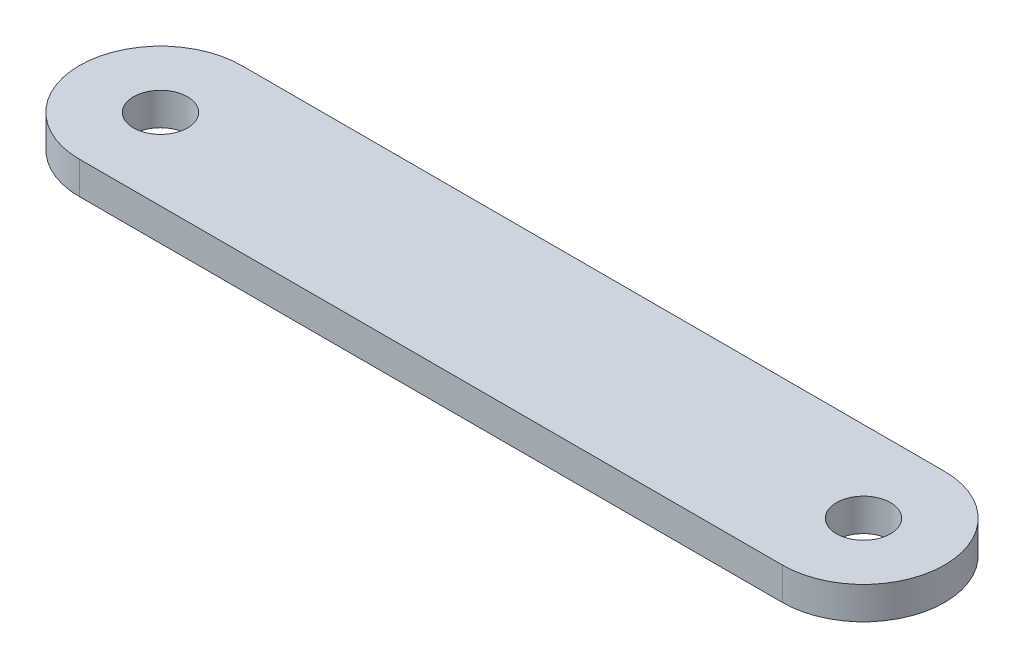
SolidWorks part; units mm, degrees
ref_plane "Front Plane" through (0, 0, 0) normal (0, 0, 1) x (1, 0, 0)
ref_plane "Top Plane" through (0, 0, 0) normal (0, 1, 0) x (1, 0, 0)
ref_plane "Right Plane" through (0, 0, 0) normal (1, 0, 0) x (0, 0, -1)
sketch "Sketch2" plane through (0, 0, 0) normal (0, 1, 0) x (1, 0, 0)
  line L1 (-6.5, 28.5) -> (123.5, 28.5)
  line L3 (-6.5, -1.5) -> (123.5, -1.5)
  arc A0 (-6.5, 28.5) -> (-6.5, -1.5) centre (-6.5, 13.5) ccw
  circle A1 centre (-6.5, 13.5) radius 5
  arc A2 (123.5, -1.5) -> (123.5, 28.5) centre (123.5, 13.5) ccw
  circle A3 centre (123.5, 13.5) radius 5
  point P0 (0, 0)
  point P9 (0, 0)
extrude "Boss-Extrude1" add sketch "Sketch2" along normal blind 6
